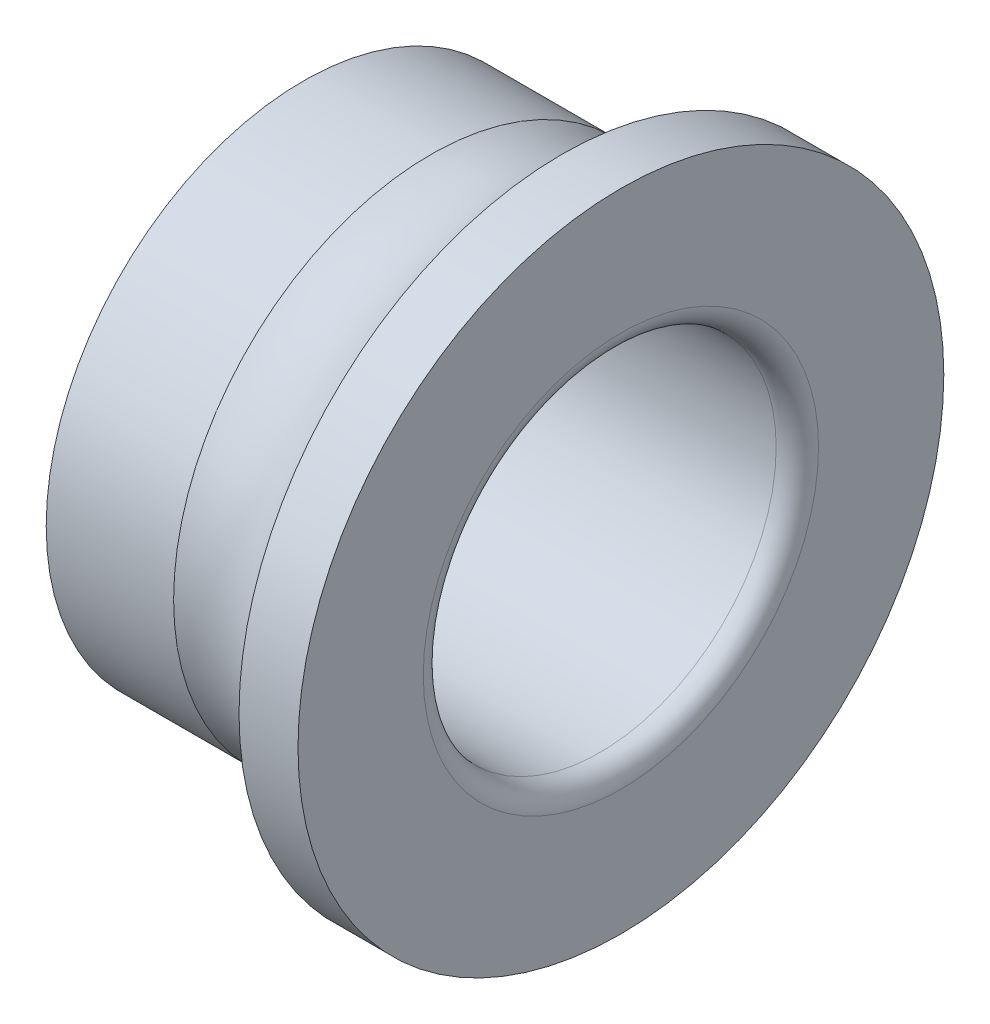
SolidWorks part; units mm, degrees
ref_plane "Front Plane" through (0, 0, 0) normal (0, 0, 1) x (1, 0, 0)
ref_plane "Top Plane" through (0, 0, 0) normal (0, 1, 0) x (1, 0, 0)
ref_plane "Right Plane" through (0, 0, 0) normal (1, 0, 0) x (0, 0, -1)
ref_plane "Plane1" through (0, 0, 0) normal (0, 0, 1) x (1, 0, 0)
sketch "Sketch1" plane through (0, 0, 0) normal (0, 0, 1) x (1, 0, 0)
  line L0 (0, 7.285) -> (0, 5.6)
  line L1 (0.6, 5) -> (8.4, 5)
  line L2 (9, 5.6) -> (9, 9.15)
  line L3 (9, 9.15) -> (7.3284, 9.15)
  line L4 (3.6102, 7.285) -> (0, 7.285)
  line L5 (9, 0) -> (0, 0) construction
  arc A0 (0, 5.6) -> (0.6, 5) centre (0.6, 5.6) ccw
  arc A1 (8.4, 5) -> (9, 5.6) centre (8.4, 5.6) ccw
  arc A2 (7.3284, 9.15) -> (3.6102, 7.285) centre (4.5, 10.15) cw
revolve "Revolve1" add sketch "Sketch1" angle 360 about L5
